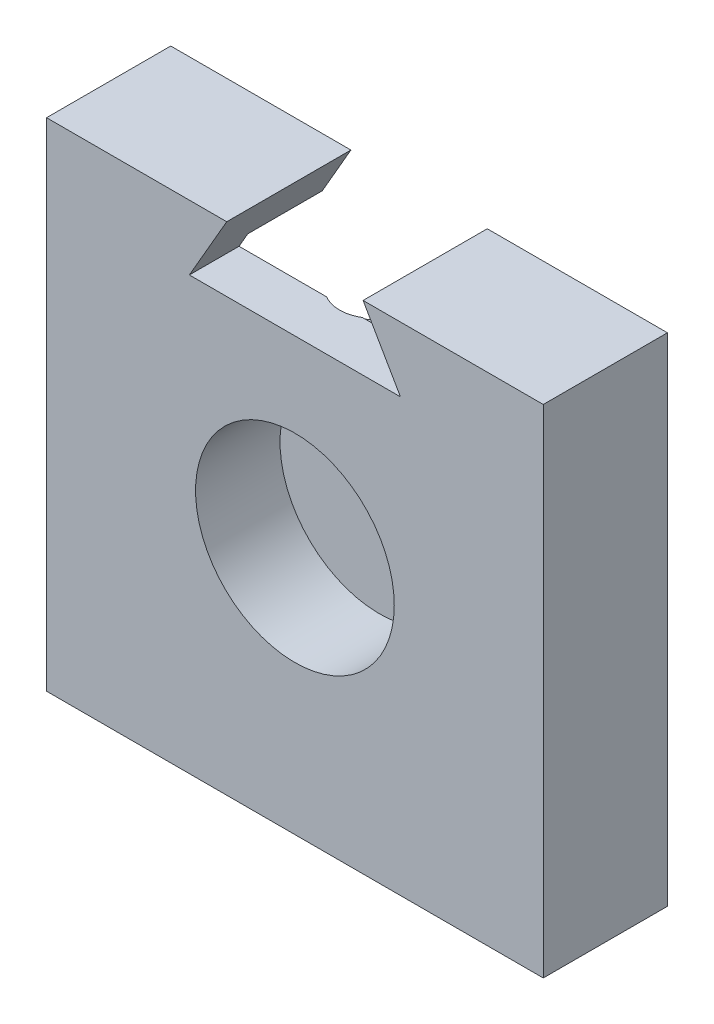
SolidWorks part; units mm, degrees
ref_plane "Front Plane" through (0, 0, 0) normal (0, 0, 1) x (1, 0, 0)
ref_plane "Top Plane" through (0, 0, 0) normal (0, 1, 0) x (1, 0, 0)
ref_plane "Right Plane" through (0, 0, 0) normal (1, 0, 0) x (0, 0, -1)
sketch "Sketch2" plane through (0, 0, 0) normal (0, 0, 1) x (1, 0, 0)
  line L0 (59.3211, -25.0679) -> (59.3211, -225.0679)
  line L1 (59.3211, -225.0679) -> (-140.6789, -225.0679)
  line L2 (-140.6789, -225.0679) -> (-140.6789, -25.0679)
  line L3 (-140.6789, -25.0679) -> (59.3211, -25.0679)
  dimension "D2" = 200
extrude "Boss-Extrude1" add sketch "Sketch2" against normal blind 50 contours L2 L3 L0 L1
shell "Shell1" thickness 20
sketch "Sketch3" plane through (0, 0, 0) normal (0, 0, 1) x (1, 0, 0)
  line L0 (-13.2286, -25.0679) -> (1.8211, -51.1576)
  line L1 (-68.1293, -25.0679) -> (-140.6789, -25.0679) construction
  line L2 (-13.2286, -25.0679) -> (59.3211, -25.0679) construction
  line L3 (1.8211, -51.1576) -> (-83.1789, -51.1576)
  line L4 (-83.1789, -51.1576) -> (-68.1293, -25.0679)
  line L5 (-140.6789, -25.0679) -> (59.3211, -25.0679) construction
  line L6 (-68.1293, -25.0679) -> (-13.2286, -25.0679)
  point P2 (-83.9318, -51.0757)
  point P4 (-68.3644, -25.0679)
extrude "Cut-Extrude1" cut sketch "Sketch3" against normal blind 50
sketch "Sketch5" plane through (0, 0, -20) normal (0, 0, -1) x (-1, 0, 0)
  circle A0 centre (40.6789, -125.0679) radius 50
extrude "Boss-Extrude2" add sketch "Sketch5" along normal blind 28
sketch "Sketch6" plane through (0, 0, 0) normal (0, 0, 1) x (1, 0, 0)
  circle A0 centre (-40.6789, -125.0679) radius 40
  circle A1 centre (-40.6789, -125.0679) radius 50 construction
extrude "Cut-Extrude2" cut sketch "Sketch6" against normal blind 34
sketch "Sketch7" plane through (0, -45.0679, 0) normal (0, -1, 0) x (-1, 0, 0)
  line L0 (1.6917, 50) -> (79.6662, 50) construction
  line L1 (79.6662, 50) -> (79.6662, 20) construction
  line L2 (40.6789, 32) -> (79.6662, 35) construction
  line L3 (40.6789, 32) -> (40.6789, 50) construction
  line L4 (1.6917, 50) -> (1.6917, 20) construction
  line L5 (40.6789, 32) -> (1.6917, 35) construction
  circle A0 centre (40.6789, 32) radius 14
extrude "Cut-Extrude4" cut sketch "Sketch7" along normal blind 46 contours A0
